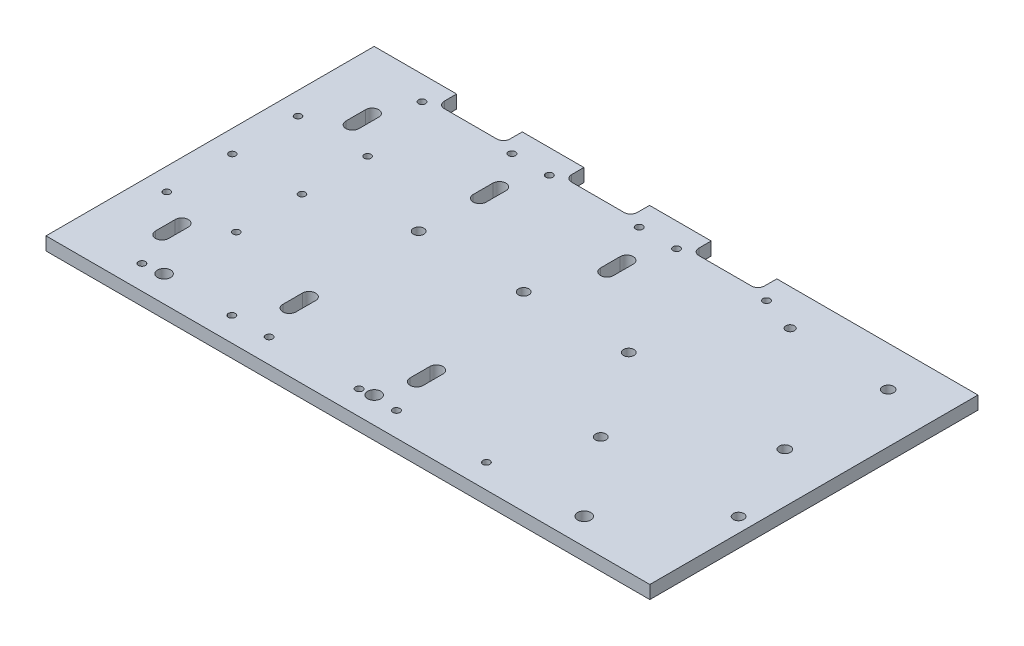
SolidWorks part; units mm, degrees
ref_plane "Front Plane" through (0, 0, 0) normal (0, 0, 1) x (1, 0, 0)
ref_plane "Top Plane" through (0, 0, 0) normal (0, 1, 0) x (1, 0, 0)
ref_plane "Right Plane" through (0, 0, 0) normal (1, 0, 0) x (0, 0, -1)
sketch "Sketch1" plane through (0, 0, 0) normal (0, 1, 0) x (1, 0, 0)
  line L1 (0, 0) -> (292.1, 0)
  line L2 (0, 0) -> (0, 158.75)
  line L3 (0, 158.75) -> (292.1, 158.75)
  line L4 (292.1, 0) -> (292.1, 158.75)
  dimension "D1" = 292.1
  dimension "D2" = 158.75
extrude "Boss-Extrude1" add sketch "Sketch1" along normal blind 6.35
sketch "Sketch2" plane through (0, 6.35, 0) normal (0, 1, 0) x (1, 0, 0)
  line L0 (0, 25.4) -> (292.1, 25.4) construction
  line L1 (0, 12.7) -> (292.1, 12.7) construction
  line L3 (146.05, 25.4) -> (146.05, 158.75) construction
  line L4 (0, 158.75) -> (0, 0)
  line L5 (0, 0) -> (292.1, 0)
  line L6 (292.1, 0) -> (292.1, 158.75)
  line L7 (292.1, 158.75) -> (0, 158.75)
  line L8 (0, 158.75) -> (0, 0) construction
  line L9 (0, 0) -> (292.1, 0) construction
  line L10 (292.1, 0) -> (292.1, 158.75) construction
  line L11 (292.1, 158.75) -> (0, 158.75) construction
  line L12 (292.1, 92.075) -> (0, 92.075) construction
  circle A0 centre (146.05, 12.7) radius 3.175
  circle A1 centre (247.65, 12.7) radius 3.175
  circle A2 centre (44.45, 12.7) radius 3.175
  point P8 (146.05, 92.075)
  dimension "D6" = 6.35
  dimension "D7" = 6.35
  dimension "D8" = 6.35
  dimension "D2" = 25.4
  dimension "D3" = 12.7
  dimension "D4" = 101.6
  dimension "D5" = 101.6
  dimension "D1" = 0
extrude "Cut-Extrude2" cut sketch "Sketch2" against normal blind 6.35
ref_plane "Plane2" through (0, 0, -79.375) normal (0, 0, 1) x (1, 0, 0)
ref_plane "Plane3" through (146.05, 0, 0) normal (-1, 0, 0) x (0, 0, 1)
ref_plane "Plane4" through (0, 0, -92.075) normal (0, 0, -1) x (-1, 0, 0)
sketch "Sketch4" plane through (0, 6.35, 0) normal (0, 1, 0) x (1, 0, 0)
  line L0 (92.964, 94.615) -> (83.439, 94.615) construction
  line L1 (83.439, 89.535) -> (92.964, 89.535) construction
  line L2 (143.764, 94.615) -> (134.239, 94.615) construction
  line L3 (134.239, 89.535) -> (143.764, 89.535) construction
  line L4 (194.564, 94.615) -> (185.039, 94.615) construction
  line L5 (185.039, 89.535) -> (194.564, 89.535) construction
  line L6 (270.764, 94.133) -> (270.764, 84.467) construction
  line L7 (265.43, 84.467) -> (265.43, 94.133) construction
  line L8 (265.43, 134.467) -> (265.43, 144.133) construction
  line L9 (270.764, 144.133) -> (270.764, 134.467) construction
  line L10 (211.4042, 52.4764) -> (218.4146, 52.4764)
  line L11 (211.4042, 74.4728) -> (211.4042, 52.4764)
  line L12 (292.1, 74.4728) -> (211.4042, 74.4728)
  line L13 (292.1, 52.4764) -> (292.1, 74.4728)
  line L14 (285.0896, 52.4764) -> (292.1, 52.4764)
  line L15 (292.1, 47.3964) -> (285.0896, 47.3964)
  line L16 (292.1, 25.4) -> (292.1, 47.3964)
  line L17 (211.4042, 25.4) -> (292.1, 25.4)
  line L18 (211.4042, 47.3964) -> (211.4042, 25.4)
  line L19 (218.4146, 47.3964) -> (211.4042, 47.3964)
  line L20 (211.4042, 52.4764) -> (218.4146, 52.4764) construction
  line L21 (211.4042, 74.4728) -> (211.4042, 52.4764) construction
  line L22 (292.1, 74.4728) -> (211.4042, 74.4728) construction
  line L23 (292.1, 52.4764) -> (292.1, 74.4728) construction
  line L24 (285.0896, 52.4764) -> (292.1, 52.4764) construction
  line L25 (292.1, 47.3964) -> (285.0896, 47.3964) construction
  line L26 (292.1, 25.4) -> (292.1, 47.3964) construction
  line L27 (211.4042, 25.4) -> (292.1, 25.4) construction
  line L28 (211.4042, 47.3964) -> (211.4042, 25.4) construction
  line L29 (218.4146, 47.3964) -> (211.4042, 47.3964) construction
  line L30 (92.964, 94.615) -> (83.439, 94.615) construction
  line L31 (83.439, 89.535) -> (92.964, 89.535) construction
  line L32 (143.764, 94.615) -> (134.239, 94.615) construction
  line L33 (134.239, 89.535) -> (143.764, 89.535) construction
  line L34 (194.564, 94.615) -> (185.039, 94.615) construction
  line L35 (185.039, 89.535) -> (194.564, 89.535) construction
  line L36 (270.764, 94.133) -> (270.764, 84.467) construction
  line L37 (265.43, 84.467) -> (265.43, 94.133) construction
  line L38 (265.43, 134.467) -> (265.43, 144.133) construction
  line L39 (270.764, 144.133) -> (270.764, 134.467) construction
  line L40 (194.564, 92.075) -> (185.039, 92.075) construction
  line L41 (185.039, 92.075) -> (143.764, 92.075) construction
  line L42 (143.764, 92.075) -> (134.239, 92.075) construction
  line L43 (134.239, 92.075) -> (92.964, 92.075) construction
  line L44 (92.964, 92.075) -> (83.439, 92.075) construction
  line L45 (268.097, 84.467) -> (268.097, 94.133) construction
  line L46 (268.097, 94.133) -> (268.097, 134.467) construction
  line L47 (268.097, 134.467) -> (268.097, 144.133) construction
  line L48 (80.7664, 149.625) -> (80.7664, 9.125) construction
  line L49 (80.7664, 9.125) -> (30.7664, 9.125) construction
  line L50 (30.7664, 9.125) -> (30.7664, 149.625) construction
  line L51 (30.7664, 149.625) -> (80.7664, 149.625) construction
  line L52 (203.9042, 9.125) -> (203.9042, 149.625)
  line L53 (153.9042, 9.125) -> (203.9042, 9.125)
  line L54 (153.9042, 149.625) -> (153.9042, 9.125)
  line L55 (203.9042, 149.625) -> (153.9042, 149.625)
  line L56 (203.9042, 9.125) -> (203.9042, 149.625) construction
  line L57 (153.9042, 9.125) -> (203.9042, 9.125) construction
  line L58 (153.9042, 149.625) -> (153.9042, 9.125) construction
  line L59 (203.9042, 149.625) -> (153.9042, 149.625) construction
  line L60 (142.3353, 149.625) -> (142.3353, 9.125) construction
  line L61 (142.3353, 9.125) -> (92.3353, 9.125) construction
  line L62 (92.3353, 9.125) -> (92.3353, 149.625) construction
  line L63 (92.3353, 149.625) -> (142.3353, 149.625) construction
  line L64 (80.7664, 149.625) -> (80.7664, 9.125) construction
  line L65 (80.7664, 9.125) -> (30.7664, 9.125) construction
  line L66 (30.7664, 9.125) -> (30.7664, 149.625) construction
  line L67 (30.7664, 149.625) -> (80.7664, 149.625) construction
  line L68 (142.3353, 149.625) -> (142.3353, 9.125) construction
  line L69 (142.3353, 9.125) -> (92.3353, 9.125) construction
  line L70 (92.3353, 9.125) -> (92.3353, 149.625) construction
  line L71 (92.3353, 149.625) -> (142.3353, 149.625) construction
  line L72 (89.1603, 130.175) -> (89.1603, 120.65) construction
  line L73 (92.3353, 130.175) -> (92.3353, 120.65)
  line L74 (85.9853, 130.175) -> (85.9853, 120.65)
  line L75 (27.5914, 130.175) -> (27.5914, 120.65) construction
  line L76 (30.7664, 130.175) -> (30.7664, 120.65)
  line L77 (24.4164, 130.175) -> (24.4164, 120.65)
  line L78 (150.7292, 130.175) -> (150.7292, 120.65) construction
  line L79 (153.9042, 130.175) -> (153.9042, 120.65)
  line L80 (147.5542, 130.175) -> (147.5542, 120.65)
  line L81 (89.1603, 130.175) -> (150.7292, 130.175) construction
  line L82 (150.7292, 38.1) -> (150.7292, 28.575) construction
  line L83 (153.9042, 38.1) -> (153.9042, 28.575)
  line L84 (147.5542, 38.1) -> (147.5542, 28.575)
  line L85 (27.5914, 38.1) -> (27.5914, 28.575) construction
  line L86 (30.7664, 38.1) -> (30.7664, 28.575)
  line L87 (24.4164, 38.1) -> (24.4164, 28.575)
  line L88 (89.1603, 38.1) -> (89.1603, 28.575) construction
  line L89 (92.3353, 38.1) -> (92.3353, 28.575)
  line L90 (85.9853, 38.1) -> (85.9853, 28.575)
  line L91 (89.1603, 28.575) -> (27.5914, 28.575) construction
  line L92 (27.5914, 28.575) -> (87.842, 28.575) construction
  line L93 (89.1603, 120.65) -> (89.1603, 38.1) construction
  line L94 (27.5914, 120.65) -> (27.5914, 38.1) construction
  line L95 (150.7292, 120.65) -> (150.7292, 69.0871) construction
  line L96 (292.1, 25.4) -> (0, 25.4) construction
  line L97 (292.1, 25.4) -> (0, 25.4) construction
  line L98 (68.4664, 152.8) -> (43.0664, 152.8) construction
  line L99 (68.4664, 149.625) -> (43.0664, 149.625)
  line L100 (76.2, 117.475) -> (215.9, 117.475) construction
  line L101 (101.4603, 152.8) -> (101.4603, 158.75)
  line L102 (133.2103, 152.8) -> (133.2103, 158.75)
  line L103 (76.2, 117.475) -> (215.9, 117.475) construction
  line L104 (71.6414, 158.75) -> (39.8914, 158.75)
  line L105 (133.2103, 158.75) -> (101.4603, 158.75)
  line L106 (194.7792, 158.75) -> (163.0292, 158.75)
  line L107 (55.7664, 149.625) -> (55.7664, 158.75) construction
  line L108 (117.3353, 149.625) -> (117.3353, 158.75) construction
  line L109 (178.9042, 149.625) -> (178.9042, 158.75) construction
  line L110 (117.3353, 149.625) -> (117.3353, 158.75) construction
  line L111 (130.0353, 152.8) -> (104.6353, 152.8) construction
  line L112 (39.8914, 152.8) -> (39.8914, 158.75)
  line L113 (71.6414, 152.8) -> (71.6414, 158.75)
  line L118 (0, 133.35) -> (292.1, 133.35) construction
  line L119 (0, 158.75) -> (0, 0) construction
  line L120 (292.1, 0) -> (292.1, 158.75) construction
  line L121 (292.1, 158.75) -> (0, 158.75) construction
  line L127 (130.0353, 149.625) -> (104.6353, 149.625)
  line L129 (178.9042, 149.625) -> (178.9042, 158.75) construction
  line L130 (163.0292, 152.8) -> (163.0292, 158.75)
  line L131 (191.6042, 152.8) -> (166.2042, 152.8) construction
  line L132 (194.7792, 152.8) -> (194.7792, 158.75)
  line L133 (191.6042, 149.625) -> (166.2042, 149.625)
  line L144 (150.7292, 69.0871) -> (150.7292, 3.6827) construction
  line L173 (216.6042, 149.625) -> (216.6042, 9.125) construction
  circle A0 centre (88.2015, 92.075) radius 2.54
  arc A1 (92.964, 89.535) -> (92.964, 94.615) centre (92.964, 92.075) ccw construction
  arc A2 (83.439, 94.615) -> (83.439, 89.535) centre (83.439, 92.075) ccw construction
  arc A3 (285.0896, 52.4764) -> (285.0896, 47.3964) centre (285.0896, 49.9364) ccw
  arc A4 (218.4146, 47.3964) -> (218.4146, 52.4764) centre (218.4146, 49.9364) ccw
  arc A5 (285.0896, 52.4764) -> (285.0896, 47.3964) centre (285.0896, 49.9364) ccw construction
  arc A6 (218.4146, 47.3964) -> (218.4146, 52.4764) centre (218.4146, 49.9364) ccw construction
  arc A7 (134.239, 94.615) -> (134.239, 89.535) centre (134.239, 92.075) ccw construction
  arc A8 (143.764, 89.535) -> (143.764, 94.615) centre (143.764, 92.075) ccw construction
  arc A9 (185.039, 94.615) -> (185.039, 89.535) centre (185.039, 92.075) ccw construction
  arc A10 (194.564, 89.535) -> (194.564, 94.615) centre (194.564, 92.075) ccw construction
  arc A11 (265.43, 84.467) -> (270.764, 84.467) centre (268.097, 84.467) ccw construction
  arc A12 (270.764, 94.133) -> (265.43, 94.133) centre (268.097, 94.133) ccw construction
  arc A13 (265.43, 134.467) -> (270.764, 134.467) centre (268.097, 134.467) ccw construction
  arc A14 (270.764, 144.133) -> (265.43, 144.133) centre (268.097, 144.133) ccw construction
  arc A15 (92.964, 89.535) -> (92.964, 94.615) centre (92.964, 92.075) ccw construction
  arc A16 (83.439, 94.615) -> (83.439, 89.535) centre (83.439, 92.075) ccw construction
  arc A17 (134.239, 94.615) -> (134.239, 89.535) centre (134.239, 92.075) ccw construction
  arc A18 (143.764, 89.535) -> (143.764, 94.615) centre (143.764, 92.075) ccw construction
  arc A19 (185.039, 94.615) -> (185.039, 89.535) centre (185.039, 92.075) ccw construction
  arc A20 (194.564, 89.535) -> (194.564, 94.615) centre (194.564, 92.075) ccw construction
  arc A21 (265.43, 84.467) -> (270.764, 84.467) centre (268.097, 84.467) ccw construction
  arc A22 (270.764, 94.133) -> (265.43, 94.133) centre (268.097, 94.133) ccw construction
  arc A23 (265.43, 134.467) -> (270.764, 134.467) centre (268.097, 134.467) ccw construction
  arc A24 (270.764, 144.133) -> (265.43, 144.133) centre (268.097, 144.133) ccw construction
  circle A25 centre (44.45, 111.125) radius 1.651 construction
  circle A26 centre (44.45, 79.375) radius 1.651 construction
  circle A27 centre (44.45, 47.625) radius 1.651 construction
  circle A28 centre (10.795, 111.125) radius 1.651 construction
  circle A29 centre (10.795, 79.375) radius 1.651 construction
  circle A30 centre (10.795, 47.625) radius 1.651 construction
  circle A31 centre (44.45, 111.125) radius 1.651
  circle A32 centre (44.45, 79.375) radius 1.651
  circle A33 centre (44.45, 47.625) radius 1.651
  circle A34 centre (10.795, 111.125) radius 1.651
  circle A35 centre (10.795, 79.375) radius 1.651
  circle A36 centre (10.795, 47.625) radius 1.651
  circle A37 centre (139.0015, 92.075) radius 2.54
  circle A38 centre (189.8015, 92.075) radius 2.54
  circle A39 centre (218.4146, 49.9364) radius 2.54
  circle A40 centre (285.0896, 49.9364) radius 2.54
  circle A41 centre (268.097, 139.3) radius 2.667
  circle A42 centre (268.097, 89.3) radius 2.667
  arc A43 (92.3353, 130.175) -> (85.9853, 130.175) centre (89.1603, 130.175) ccw
  arc A44 (85.9853, 120.65) -> (92.3353, 120.65) centre (89.1603, 120.65) ccw
  arc A45 (30.7664, 130.175) -> (24.4164, 130.175) centre (27.5914, 130.175) ccw
  arc A46 (24.4164, 120.65) -> (30.7664, 120.65) centre (27.5914, 120.65) ccw
  arc A47 (153.9042, 130.175) -> (147.5542, 130.175) centre (150.7292, 130.175) ccw
  arc A48 (147.5542, 120.65) -> (153.9042, 120.65) centre (150.7292, 120.65) ccw
  arc A49 (153.9042, 38.1) -> (147.5542, 38.1) centre (150.7292, 38.1) ccw
  arc A50 (147.5542, 28.575) -> (153.9042, 28.575) centre (150.7292, 28.575) ccw
  arc A51 (30.7664, 38.1) -> (24.4164, 38.1) centre (27.5914, 38.1) ccw
  arc A52 (24.4164, 28.575) -> (30.7664, 28.575) centre (27.5914, 28.575) ccw
  arc A53 (92.3353, 38.1) -> (85.9853, 38.1) centre (89.1603, 38.1) ccw
  arc A54 (85.9853, 28.575) -> (92.3353, 28.575) centre (89.1603, 28.575) ccw
  arc A55 (71.6414, 152.8) -> (68.4664, 149.625) centre (68.4664, 152.8) cw
  arc A56 (39.8914, 152.8) -> (43.0664, 149.625) centre (43.0664, 152.8) ccw
  circle A57 centre (201.4042, 147.125) radius 1.7 construction
  circle A58 centre (157.9042, 147.125) radius 1.7 construction
  circle A59 centre (139.8353, 147.125) radius 1.7 construction
  circle A60 centre (96.3353, 147.125) radius 1.7 construction
  arc A61 (133.2103, 152.8) -> (130.0353, 149.625) centre (130.0353, 152.8) cw
  arc A62 (101.4603, 152.8) -> (104.6353, 149.625) centre (104.6353, 152.8) ccw
  arc A63 (194.7792, 152.8) -> (191.6042, 149.625) centre (191.6042, 152.8) cw
  arc A64 (163.0292, 152.8) -> (166.2042, 149.625) centre (166.2042, 152.8) ccw
  circle A65 centre (78.2664, 147.125) radius 1.7 construction
  circle A66 centre (34.7664, 147.125) radius 1.7 construction
  circle A67 centre (157.9042, 11.625) radius 1.7 construction
  circle A68 centre (201.4042, 11.625) radius 1.7 construction
  circle A69 centre (139.8353, 11.625) radius 1.7 construction
  circle A70 centre (96.3353, 11.625) radius 1.7 construction
  circle A71 centre (78.2664, 11.625) radius 1.7 construction
  circle A72 centre (34.7664, 11.625) radius 1.7 construction
  circle A73 centre (201.4042, 147.125) radius 1.7
  circle A74 centre (157.9042, 147.125) radius 1.7
  circle A75 centre (139.8353, 147.125) radius 1.7
  circle A76 centre (96.3353, 147.125) radius 1.7
  circle A77 centre (78.2664, 147.125) radius 1.7
  circle A78 centre (34.7664, 147.125) radius 1.7
  circle A79 centre (157.9042, 11.625) radius 1.7
  circle A80 centre (201.4042, 11.625) radius 1.7
  circle A81 centre (139.8353, 11.625) radius 1.7
  circle A82 centre (96.3353, 11.625) radius 1.7
  circle A83 centre (78.2664, 11.625) radius 1.7
  circle A84 centre (34.7664, 11.625) radius 1.7
  circle A93 centre (218.6997, 141.2875) radius 2.0955 construction
  circle A94 centre (218.6997, 141.2875) radius 2.0955
  point P100 (89.1603, 125.4125)
  point P105 (27.5914, 125.4125)
  point P112 (150.7292, 125.4125)
  point P121 (150.7292, 33.3375)
  point P128 (27.5914, 33.3375)
  point P135 (89.1603, 33.3375)
  point P142 (89.1603, 25.4)
  point P152 (55.7664, 152.8)
  point P159 (117.3353, 152.8)
  point P211 (178.9042, 152.8)
  dimension "D3" = 3.175
  dimension "D5" = 3.175
  dimension "D8" = 3.175
  dimension "D10" = 3.175
  dimension "D4" = 25.4
  dimension "D6" = 25.4
  dimension "D7" = 25.4
  dimension "D9" = 25.4
  dimension "D11" = 12.7
  dimension "D1" = 0
  dimension "D2" = 0
extrude "Cut-Extrude5" cut sketch "Sketch4" against normal through all
equation "\"D5@Sketch2\"=\"D4@Sketch2\""
equation "\"D7@Sketch2\"=\"D6@Sketch2\""
equation "\"D8@Sketch2\"=\"D7@Sketch2\""
